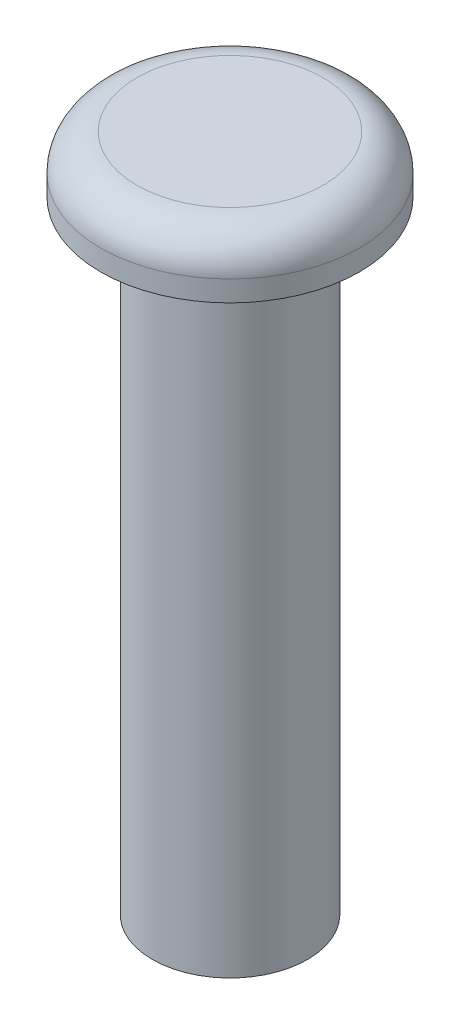
SolidWorks part; units mm, degrees
ref_plane "前视基准面" through (0, 0, 0) normal (0, 0, 1) x (1, 0, 0)
ref_plane "上视基准面" through (0, 0, 0) normal (0, 1, 0) x (1, 0, 0)
ref_plane "右视基准面" through (0, 0, 0) normal (1, 0, 0) x (0, 0, -1)
sketch "草图1" plane through (0, 0, 0) normal (0, 1, 0) x (1, 0, 0)
  circle A0 centre (0, 0) radius 1.5
extrude "凸台-拉伸1" add sketch "草图1" along normal blind 12
sketch "草图2" plane through (0, 12, 0) normal (0, 1, 0) x (1, 0, 0)
  circle A0 centre (0, 0) radius 2.5
extrude "凸台-拉伸2" add sketch "草图2" along normal blind 1.1
fillet "圆角1" radius 0.7 1 edges at (0, 13.1, 2.5)
